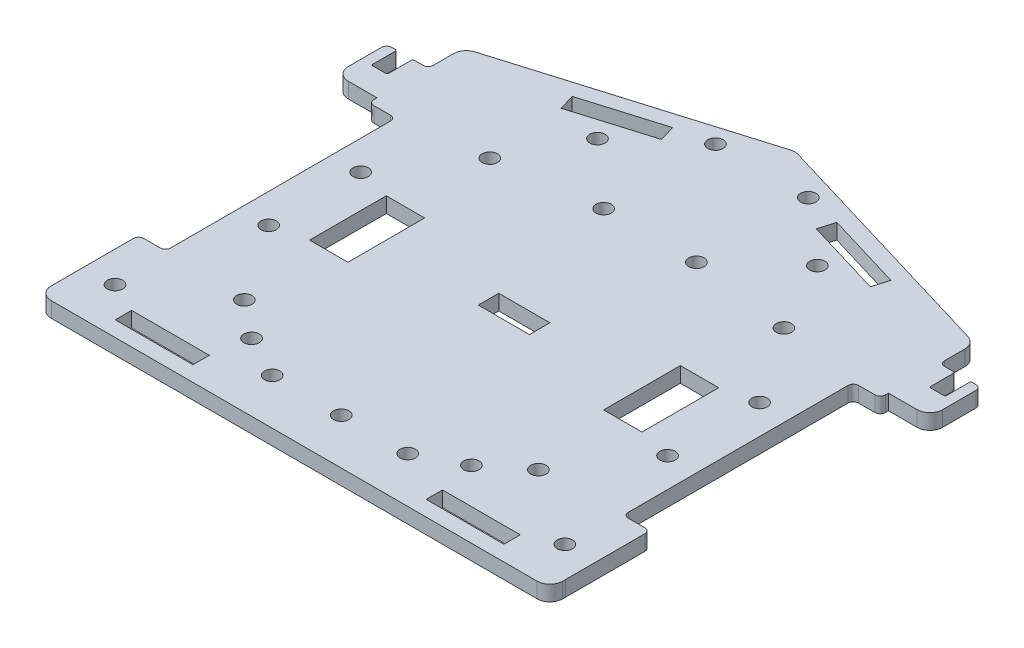
SolidWorks part; units mm, degrees
ref_plane "Alzado" through (0, 0, 0) normal (0, 0, 1) x (1, 0, 0)
ref_plane "Planta" through (0, 0, 0) normal (0, 1, 0) x (1, 0, 0)
ref_plane "Vista lateral" through (0, 0, 0) normal (1, 0, 0) x (0, 0, -1)
sketch "Croquis3" plane through (0, 0, 0) normal (0, 1, 0) x (1, 0, 0)
  line L0 (-23.5, 40) -> (23.5, 40) construction
  line L3 (-50, -40) -> (50, -40)
  line L5 (-50, 40) -> (50, -40) construction
  line L6 (-50, -40) -> (50, 40) construction
  line L7 (-48.2184, 40.5345) -> (-0.7184, 54.7845)
  line L8 (0.7184, 54.7845) -> (48.2184, 40.5345)
  line L9 (23.5, 40) -> (23.5, -32) construction
  line L14 (23.5, -32) -> (-23.5, -32) construction
  line L16 (-23.5, -32) -> (-23.5, 40) construction
  line L17 (0, 7.5742) -> (0, -7.5742) construction
  line L18 (-8.1342, 0) -> (8.1342, 0) construction
  line L19 (-21.5334, 37.8306) -> (21.4666, 37.8306) construction
  line L20 (21.4666, 38.1883) -> (21.4666, -29.8117) construction
  line L21 (5, 0) -> (25, 0) construction
  line L22 (-5, 2) -> (5, 2)
  line L23 (-5, 2) -> (-5, -2)
  line L24 (-5, -2) -> (5, -2)
  line L25 (5, 2) -> (5, -2)
  line L26 (-5, 2) -> (5, -2) construction
  line L27 (-5, -2) -> (5, 2) construction
  line L28 (25, 7.5) -> (25, -7.5)
  line L29 (25, -7.5) -> (32.5, -7.5)
  line L30 (32.5, -7.5) -> (32.5, 7.5)
  line L31 (32.5, 7.5) -> (25, 7.5)
  line L32 (-32.5, -7.5) -> (-32.5, 7.5)
  line L33 (-25, -7.5) -> (-32.5, -7.5)
  line L34 (-25, 7.5) -> (-25, -7.5)
  line L35 (-32.5, 7.5) -> (-25, 7.5)
  line L36 (-24.4684, 47.6595) -> (-23.6063, 44.786) construction
  line L37 (-31.1563, 42.521) -> (-16.0563, 47.051)
  line L38 (-16.0563, 47.051) -> (-15.1263, 43.951)
  line L39 (-15.1263, 43.951) -> (-30.2263, 39.421)
  line L40 (-30.2263, 39.421) -> (-31.1563, 42.521)
  line L41 (15.1263, 43.951) -> (30.2263, 39.421)
  line L42 (16.0563, 47.051) -> (15.1263, 43.951)
  line L43 (31.1563, 42.521) -> (16.0563, 47.051)
  line L44 (30.2263, 39.421) -> (31.1563, 42.521)
  line L45 (-50, 33.1899) -> (-47, 33.1899) construction
  line L46 (-50, 33.1899) -> (-53, 33.1899)
  line L47 (-53, 33.1899) -> (-53, 28.1899)
  line L48 (-53, 28.1899) -> (-56.1, 28.1899)
  line L49 (-56.1, 28.1899) -> (-56.1, 33.1899)
  line L50 (-56.1, 33.1899) -> (-58.1, 33.1899)
  line L51 (-58.1, 33.1899) -> (-58.1, 25.6899)
  line L52 (-55.6, 23.1899) -> (-50, 23.1899)
  line L53 (-50, 38.1399) -> (-50, 33.1899)
  line L54 (-50, 23.1899) -> (-50, -40)
  line L55 (50, 23.1899) -> (50, -40)
  line L56 (55.6, 23.1899) -> (50, 23.1899)
  line L57 (58.1, 33.1899) -> (58.1, 25.6899)
  line L58 (56.1, 33.1899) -> (58.1, 33.1899)
  line L59 (56.1, 28.1899) -> (56.1, 33.1899)
  line L60 (53, 28.1899) -> (56.1, 28.1899)
  line L61 (53, 33.1899) -> (53, 28.1899)
  line L62 (50, 33.1899) -> (53, 33.1899)
  line L63 (50, 38.1399) -> (50, 33.1899)
  circle A0 centre (-21.5334, 37.8306) radius 1.5
  circle A1 centre (21.4666, 37.8306) radius 1.5
  circle A2 centre (21.4666, -29.8117) radius 1.5
  circle A3 centre (-21.5334, -29.8117) radius 1.5
  arc A4 (48.2184, 40.5345) -> (50, 38.1399) centre (47.5, 38.1399) cw
  arc A5 (-48.2184, 40.5345) -> (-50, 38.1399) centre (-47.5, 38.1399) ccw
  arc A6 (0.7184, 54.7845) -> (-0.7184, 54.7845) centre (0, 52.3899) ccw
  arc A7 (-58.1, 25.6899) -> (-55.6, 23.1899) centre (-55.6, 25.6899) ccw
  arc A8 (58.1, 25.6899) -> (55.6, 23.1899) centre (55.6, 25.6899) cw
  point P0 (0, 0)
  point P11 (0, 40)
  point P16 (0, 0)
  point P18 (0, 0)
  point P21 (-0.0334, 37.8306)
  point P26 (21.4666, 4.1883)
  point P29 (0, 0)
  point P39 (25, 0)
  point P53 (0, 55)
  point P54 (-31.5, 45.55)
  point P60 (-23.6063, 44.786)
  point P66 (-50, 33.1899)
  point P78 (-58.1, 23.1899)
  point P94 (0, 40)
  dimension "D7" = 3
  dimension "D8" = 3
  dimension "D10" = 3
  dimension "D11" = 3
  dimension "D17" = 2.5
  dimension "D29" = 2.5
  dimension "D1" = 80
  dimension "D2" = 100
  dimension "D3" = 47
  dimension "D4" = 72
  dimension "D5" = 15
  dimension "D6" = 43
  dimension "D9" = 68
  dimension "D12" = 10
  dimension "D13" = 4
  dimension "D14" = 20
  dimension "D15" = 7.5
  dimension "D16" = 15
  dimension "D18" = 18.5
  dimension "D19" = 3
  dimension "D20" = 15.1
  dimension "D21" = 3.1
  dimension "D22" = 4.95
  dimension "D23" = 10
  dimension "D24" = 5
  dimension "D25" = 5
  dimension "D26" = 3.1
  dimension "D27" = 3
  dimension "D28" = 2
extrude "Saliente-Extruir1" add sketch "Croquis3" along normal blind 3
sketch "Croquis4" plane through (0, 3, 0) normal (0, 1, 0) x (1, 0, 0)
  line L0 (-32.5, 7.5) -> (-32.5, -7.5) construction
  line L1 (44.75, 21.57) -> (58.75, 21.57)
  line L2 (44.75, 21.57) -> (44.75, -23.43)
  line L3 (44.75, -23.43) -> (58.75, -23.43)
  line L4 (58.75, 21.57) -> (58.75, -23.43)
  line L5 (44.75, 21.57) -> (58.75, -23.43) construction
  line L6 (44.75, -23.43) -> (58.75, 21.57) construction
  line L7 (0, 9.5449) -> (0, -9.5449) construction
  line L8 (-44.75, -23.43) -> (-58.75, -23.43)
  line L9 (-58.75, 21.57) -> (-58.75, -23.43)
  line L10 (-44.75, 21.57) -> (-58.75, 21.57)
  line L11 (-44.75, 21.57) -> (-44.75, -23.43)
  line L12 (-28.75, 7.5) -> (-28.75, 24) construction
  line L13 (-25, 7.5) -> (-32.5, 7.5) construction
  line L14 (-8.1155, 0) -> (8.1155, 0) construction
  line L16 (-38, -40) -> (-22.8, -40)
  line L17 (-50, -40) -> (50, -40) construction
  line L18 (-38, -40) -> (-38, -36.8)
  line L19 (-38, -36.8) -> (-22.8, -36.8)
  line L20 (-22.8, -40) -> (-22.8, -36.8)
  line L24 (38, -36.8) -> (22.8, -36.8)
  line L25 (22.8, -40) -> (22.8, -36.8)
  line L26 (38, -40) -> (22.8, -40)
  line L27 (38, -40) -> (38, -36.8)
  line L28 (-22.8, -36.8) -> (-18.4677, -36.8) construction
  line L29 (-21.5334, -31.3117) -> (-21.5334, -36.8) construction
  line L30 (-1.25, -34.0559) -> (-13.25, -34.0559) construction
  line L31 (-44.75, 9) -> (-33.25, 9) construction
  line L35 (-44.75, 9) -> (-44.75, -9) construction
  line L36 (-32.75, -15.8561) -> (32.75, -15.8561) construction
  line L37 (-44.75, -9) -> (-33.25, -9) construction
  line L38 (-33.25, 9) -> (-33.25, -9) construction
  circle A1 centre (28.75, 24) radius 1.5
  circle A2 centre (-28.75, 24) radius 1.5
  circle A3 centre (28.75, -24) radius 1.5
  circle A4 centre (-28.75, -24) radius 1.5
  circle A6 centre (-21.5334, -29.8117) radius 1.5 construction
  circle A10 centre (0.25, -34.0559) radius 1.5
  circle A11 centre (-13.25, -34.0559) radius 1.5
  circle A12 centre (13.25, -34.0559) radius 1.5
  circle A18 centre (-39, 9) radius 1.5
  circle A19 centre (39, 9) radius 1.5
  circle A20 centre (39, -9) radius 1.5
  circle A21 centre (-39, -9) radius 1.5
  circle A22 centre (-43.981, -34.0559) radius 1.5
  circle A23 centre (43.981, -34.0559) radius 1.5
  point P0 (51.75, -0.93)
  point P11 (0, 0)
  point P23 (0, 0)
  point P29 (-38, -40)
  point P70 (-32.5, 0)
  point P71 (-33.25, 0)
  dimension "D4" = 3
  dimension "D6" = 3.2
  dimension "D5" = 3
  dimension "D8" = 3
  dimension "D10" = 3
  dimension "D12" = 18
  dimension "D13" = 3
  dimension "D1" = 14
  dimension "D2" = 45
  dimension "D3" = 16.5
  dimension "D7" = 15.2
  dimension "D9" = 12
  dimension "D11" = 11.5
extrude "Cortar-Extruir1" cut sketch "Croquis4" against normal mid plane 6
sketch "Croquis5" plane through (0, 0, 0) normal (0, 1, 0) x (1, 0, 0)
  line L1 (-50, -40) -> (49.9993, -40)
  line L2 (-50, -40) -> (-50, -40.5)
  line L3 (-47.5, -43) -> (47.4993, -43)
  line L4 (49.9993, -40) -> (49.9993, -40.5)
  arc A0 (47.4993, -43) -> (49.9993, -40.5) centre (47.4993, -40.5) ccw
  arc A1 (-50, -40.5) -> (-47.5, -43) centre (-47.5, -40.5) ccw
  point P7 (49.9993, -43)
  point P10 (-50, -43)
  dimension "D3" = 2.5
  dimension "D1" = 99.9993
  dimension "D2" = 3
extrude "Saliente-Extruir2" add sketch "Croquis5" along normal blind 3
fillet "Redondeo1" radius 1 12 edges at (58.1, 1.5, -33.1899) (-58.1, 1.5, -33.1899) (-50, 1.5, -21.57) (-50, 1.5, 23.43) (-44.75, 1.5, 23.43) (-44.75, 1.5, -21.57) (50, 1.5, 23.43) (44.75, 1.5, -21.57) (44.75, 1.5, 23.43) (50, 1.5, -33.1899) (-50, 1.5, -33.1899) (50, 1.5, -21.57)
fillet "Redondeo2" radius 0.25 8 edges at (53, 1.5, -28.1899) (56.1, 1.5, -28.1899) (56.1, 1.5, -33.1899) (53, 1.5, -33.1899) (-53, 1.5, -28.1899) (-56.1, 1.5, -28.1899) (-56.1, 1.5, -33.1899) (-53, 1.5, -33.1899)
sketch "Croquis9" plane through (0, 3, 0) normal (0, 1, 0) x (1, 0, 0)
  line L0 (0, 2) -> (0, 54.8899) construction
  line L1 (5, 2) -> (-5, 2) construction
  line L2 (-2.7303, 37.507) -> (1.7414, 37.507) construction
  line L3 (-7.5, 48.507) -> (7.5, 48.507) construction
  line L4 (-7.5, 48.507) -> (-7.5, 26.507) construction
  line L5 (-7.5, 26.507) -> (7.5, 26.507) construction
  line L6 (7.5, 48.507) -> (7.5, 26.507) construction
  line L7 (-7.5, 48.507) -> (7.5, 26.507) construction
  line L8 (-7.5, 26.507) -> (7.5, 48.507) construction
  line L10 (-9.8292, 51.0176) -> (9.8292, 51.0176) construction
  line L11 (-12.3292, 48.5176) -> (-12.3292, 26.4963) construction
  line L12 (-9.8292, 23.9963) -> (9.8292, 23.9963) construction
  line L13 (12.3292, 48.5176) -> (12.3292, 26.4963) construction
  line L14 (-12.3292, 51.0176) -> (12.3292, 23.9963) construction
  line L15 (-12.3292, 23.9963) -> (12.3292, 51.0176) construction
  arc A0 (0.7184, 54.7845) -> (-0.7184, 54.7845) centre (0, 52.3899) ccw construction
  circle A1 centre (0, 48.507) radius 1.4982 construction
  circle A2 centre (0, 26.507) radius 1.4982 construction
  circle A3 centre (-9.0752, 48.4415) radius 1.5
  circle A4 centre (-9.0752, 26.5724) radius 1.5
  circle A5 centre (9.0752, 26.5724) radius 1.5
  circle A6 centre (9.0752, 48.4415) radius 1.5
  arc A7 (-9.8292, 23.9963) -> (-12.3292, 26.4963) centre (-9.8292, 26.4963) cw construction
  arc A8 (9.8292, 23.9963) -> (12.3292, 26.4963) centre (9.8292, 26.4963) ccw construction
  arc A9 (9.8292, 51.0176) -> (12.3292, 48.5176) centre (9.8292, 48.5176) cw construction
  arc A10 (-9.8292, 51.0176) -> (-12.3292, 48.5176) centre (-9.8292, 48.5176) ccw construction
  point P7 (0, 37.507)
  point P26 (0, 37.507)
  dimension "D3" = 2.9964
  dimension "D4" = 3
  dimension "D5" = 2.5
  dimension "D1" = 15
  dimension "D2" = 22
extrude "Cortar-Extruir3" cut sketch "Croquis9" against normal mid plane 10
